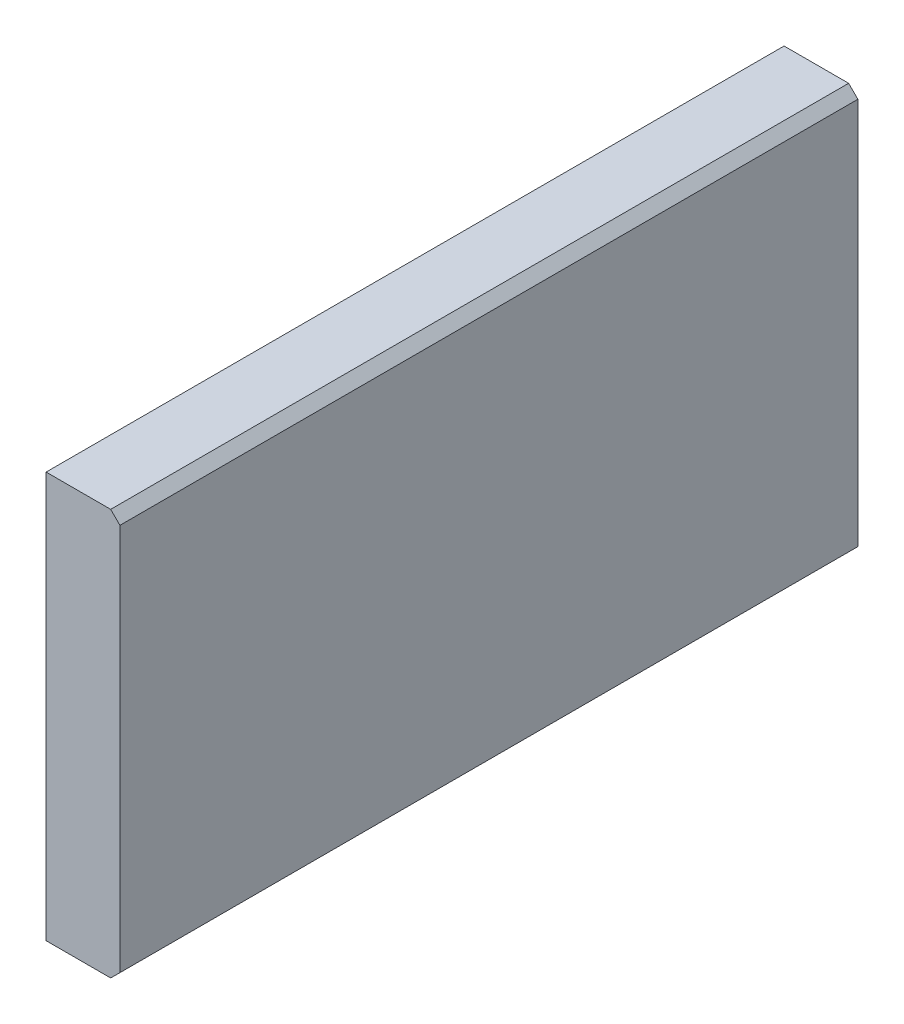
SolidWorks part; units mm, degrees
material "ABS"
ref_plane "Front Plane" through (0, 0, 0) normal (0, 0, 1) x (1, 0, 0)
ref_plane "Top Plane" through (0, 0, 0) normal (0, 1, 0) x (1, 0, 0)
ref_plane "Right Plane" through (0, 0, 0) normal (1, 0, 0) x (0, 0, -1)
ref_plane "X_WEB" through (24, 0, 0) normal (1, 0, 0) x (0, 0, -1)
sketch "Sketch1" plane through (24, 0, 0) normal (1, 0, 0) x (0, 0, -1)
  line L1 (-40, -22) -> (40, -22)
  line L2 (-40, -22) -> (-40, 22)
  line L3 (-40, 22) -> (40, 22)
  line L4 (40, -22) -> (40, 22)
extrude "Boss-Extrude1" add sketch "Sketch1" along normal blind 8
ref_plane "X+21_20" through (21.2, 0, 0) normal (1, 0, 0) x (0, 0, -1)
sketch "Sketch2" plane through (21.2, 0, 0) normal (1, 0, 0) x (0, 0, -1)
  circle A0 centre (-4, -4) radius 1.5
  circle A1 centre (4, -4) radius 1.5
  circle A2 centre (-4, 4) radius 1.5
  circle A3 centre (4, 4) radius 1.5
extrude "Boss-Extrude2" add sketch "Sketch2" along normal blind 2.8
ref_plane "X_SOLE" through (32, 0, 0) normal (1, 0, 0) x (0, 0, -1)
chamfer "Chamfer1" distance 1 angle 45 2 edges at (32, -22, 0) (32, 22, 0)
